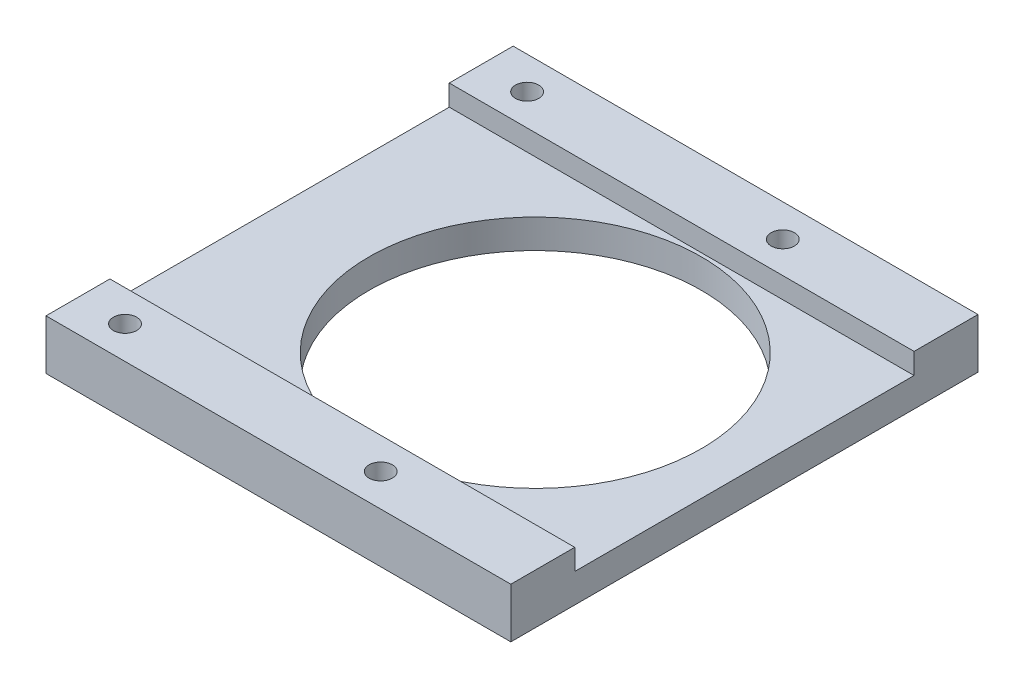
SolidWorks part; units mm, degrees
ref_plane "前视基准面" through (0, 0, 0) normal (0, 0, 1) x (1, 0, 0)
ref_plane "上视基准面" through (0, 0, 0) normal (0, 1, 0) x (1, 0, 0)
ref_plane "右视基准面" through (0, 0, 0) normal (1, 0, 0) x (0, 0, -1)
sketch "草图1" plane through (0, 0, 0) normal (0, 1, 0) x (1, 0, 0)
  line L1 (-22, 20.1) -> (18, 20.1)
  line L2 (-22, 20.1) -> (-22, -20.1)
  line L3 (-22, -20.1) -> (18, -20.1)
  line L4 (18, 20.1) -> (18, -20.1)
  circle A0 centre (0, 0) radius 14.3
  dimension "D1" = 28.6
  dimension "D2" = 18
  dimension "D3" = 22
  dimension "D4" = 40.2
  dimension "D5" = 20.1
extrude "凸台-拉伸1" add sketch "草图1" along normal blind 2.5
sketch "草图2" plane through (0, 2.5, 0) normal (0, 1, 0) x (1, 0, 0)
  line L0 (18, -20.1) -> (18, 20.1) construction
  line L1 (-22, 20.1) -> (18, 20.1)
  line L2 (-22, 20.1) -> (-22, 14.6)
  line L3 (-22, 14.6) -> (18, 14.6)
  line L4 (18, 20.1) -> (18, 14.6)
  line L6 (-22, -20.1) -> (18, -20.1)
  line L7 (-22, -20.1) -> (-22, -14.6)
  line L8 (-22, -14.6) -> (18, -14.6)
  line L9 (18, -20.1) -> (18, -14.6)
  dimension "D1" = 5.5
  dimension "D2" = 5.5
extrude "凸台-拉伸2" add sketch "草图2" along normal blind 1.8
sketch "草图3" plane through (0, 4.3, 0) normal (0, 1, 0) x (1, 0, 0)
  line L0 (-4.9349, 0) -> (4.4319, 0) construction
  line L1 (-22, 14.6) -> (18, 14.6) construction
  circle A0 centre (4, 17.3) radius 1
  circle A1 centre (-18, 17.3) radius 1
  circle A3 centre (-18, -17.3) radius 1
  circle A4 centre (4, -17.3) radius 1
  dimension "D1" = 2
  dimension "D2" = 2.7
  dimension "D3" = 4
  dimension "D4" = 22
extrude "切除-拉伸1" cut sketch "草图3" against normal up to next
